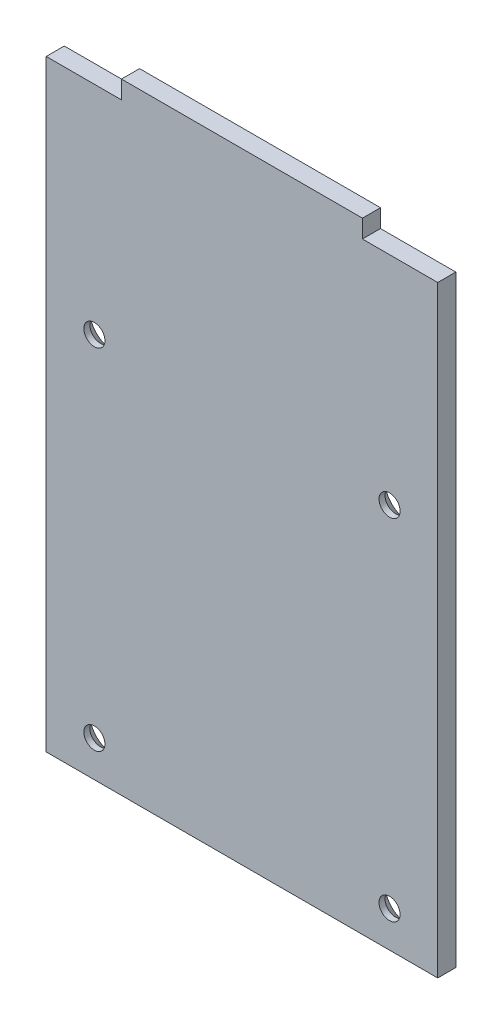
SolidWorks part; units mm, degrees
material "ABS"
ref_plane "Спереди" through (0, 0, 0) normal (0, 0, 1) x (1, 0, 0)
ref_plane "Сверху" through (0, 0, 0) normal (0, 1, 0) x (1, 0, 0)
ref_plane "Справа" through (0, 0, 0) normal (1, 0, 0) x (0, 0, -1)
sketch "Эскиз1" plane through (0, 0, 0) normal (0, 0, 1) x (1, 0, 0)
  line L1 (-32.5, -50) -> (32.5, -50)
  line L2 (-32.5, -50) -> (-32.5, 50)
  line L3 (-32.5, 50) -> (32.5, 50)
  line L4 (32.5, -50) -> (32.5, 50)
  line L5 (-32.5, -50) -> (32.5, 50) construction
  line L6 (-32.5, 50) -> (32.5, -50) construction
  line L7 (-20, 47) -> (20, 47)
  line L8 (-20, 47) -> (-20, 53)
  line L9 (-20, 53) -> (20, 53)
  line L10 (20, 47) -> (20, 53)
  line L11 (-20, 47) -> (20, 53) construction
  line L12 (-20, 53) -> (20, 47) construction
  point P0 (0, 0)
  point P6 (0, 50)
  dimension "D1" = 3
  dimension "D2" = 40
  dimension "D3" = 12.5
  dimension "D4" = 100
extrude "Бобышка-Вытянуть1" add sketch "Эскиз1" along normal blind 3 contours L10 L7 L8 L3 L2 L1 L4 | L7 L10 L3 L8 | L3 L10 L9 L8
sketch "Эскиз2" plane through (0, 0, 3) normal (0, 0, 1) x (1, 0, 0)
  line L0 (0, -50) -> (0, 53) construction
  line L1 (-32.5, -50) -> (32.5, -50) construction
  line L2 (-20, 53) -> (20, 53) construction
  line L4 (-24.5, -44) -> (24.5, -44) construction
  line L5 (-24.5, -44) -> (-24.5, 14) construction
  line L6 (-24.5, 14) -> (24.5, 14) construction
  line L7 (24.5, -44) -> (24.5, 14) construction
  line L8 (-24.5, -44) -> (24.5, 14) construction
  line L9 (-24.5, 14) -> (24.5, -44) construction
  circle A0 centre (-24.5, 14) radius 1.75
  circle A1 centre (24.5, 14) radius 1.75
  circle A2 centre (24.5, -44) radius 1.75
  circle A3 centre (-24.5, -44) radius 1.75
  point P6 (0, -15)
  dimension "D4" = 3.5
  dimension "D1" = 49
  dimension "D2" = 58
  dimension "D3" = 15
extrude "Вырез-Вытянуть1" cut sketch "Эскиз2" against normal blind 10
chamfer "Фаска1" distance 2 angle 45 4 edges at (-22.75, -44, 0) (-22.75, 14, 0) (26.25, 14, 0) (26.25, -44, 0)
